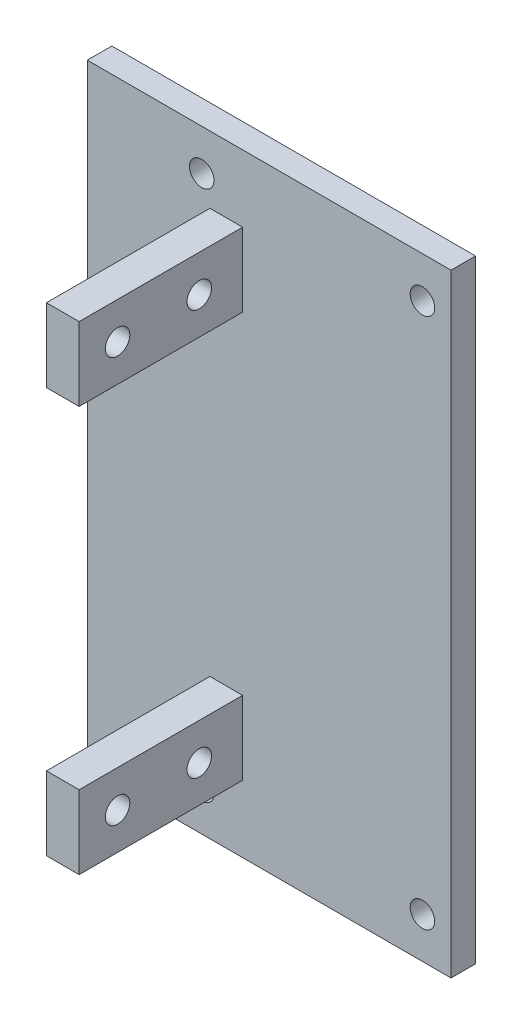
SolidWorks part; units mm, degrees
ref_plane "Front Plane" through (0, 0, 0) normal (0, 0, 1) x (1, 0, 0)
ref_plane "Top Plane" through (0, 0, 0) normal (0, 1, 0) x (1, 0, 0)
ref_plane "Right Plane" through (0, 0, 0) normal (1, 0, 0) x (0, 0, -1)
sketch "Sketch1" plane through (0, 0, 0) normal (0, 0, 1) x (1, 0, 0)
  line L0 (-11, 32.5) -> (16, 32.5) construction
  line L1 (-25, -37.5) -> (25, -37.5)
  line L2 (-25, -37.5) -> (-25, 37.5)
  line L3 (-25, 37.5) -> (25, 37.5)
  line L4 (25, -37.5) -> (25, 37.5)
  line L5 (-25, -37.5) -> (25, 37.5) construction
  line L6 (-25, 37.5) -> (25, -37.5) construction
  line L7 (16, 32.5) -> (16, -32.5) construction
  circle A0 centre (-11, 32.5) radius 1.5
  circle A1 centre (16, 32.5) radius 1.5
  circle A2 centre (16, -32.5) radius 1.5
  circle A3 centre (-11, -32.5) radius 1.5
  point P0 (0, 0)
  point P20 (16, 0)
  point P21 (25, 0)
  dimension "D3" = 3
  dimension "D1" = 50
  dimension "D2" = 75
  dimension "D4" = 27
  dimension "D5" = 65
  dimension "D6" = 14
extrude "Boss-Extrude1" add sketch "Sketch1" along normal blind 3
sketch "Sketch2" plane through (0, 0, 3) normal (0, 0, 1) x (1, 0, 0)
  line L0 (-25, 37.5) -> (-25, -37.5) construction
  line L1 (-10, 29.3) -> (-6, 29.3)
  line L2 (-10, 29.3) -> (-10, 20.3)
  line L3 (-10, 20.3) -> (-6, 20.3)
  line L4 (-6, 29.3) -> (-6, 20.3)
  dimension "D1" = 4
  dimension "D2" = 9
  dimension "D3" = 20.3
  dimension "D4" = 15
extrude "Boss-Extrude2" add sketch "Sketch2" along normal blind 20
sketch "Sketch3" plane through (-10, 0, 0) normal (-1, 0, 0) x (0, 0, 1)
  line L0 (3, 20.3) -> (3, 29.3) construction
  line L2 (23, 29.3) -> (23, 20.3) construction
  circle A0 centre (18.3, 24.8) radius 1.5
  circle A1 centre (8.3, 24.8) radius 1.5
  point P8 (23, 24.8)
  dimension "D1" = 3
  dimension "D2" = 10
  dimension "D3" = 5.3
extrude "Cut-Extrude2" cut sketch "Sketch3" against normal through all both and the other way through all
mirror "Mirror3" about plane through (0, 0, 0) normal (0, 1, 0) of "Cut-Extrude2", "Boss-Extrude2"
sketch "Sketch4" plane through (0, 0, 3) normal (0, 0, 1) x (1, 0, 0)
  line L0 (-25, -37.5) -> (25, -37.5) construction
  line L1 (25, 37.5) -> (19.5, 37.5)
  line L2 (25, 37.5) -> (25, -37.5)
  line L3 (25, -37.5) -> (19.5, -37.5)
  line L4 (19.5, 37.5) -> (19.5, -37.5)
  line L5 (25, 37.5) -> (-25, 37.5) construction
  dimension "D1" = 5.5
extrude "Cut-Extrude3" cut sketch "Sketch4" against normal blind 10
